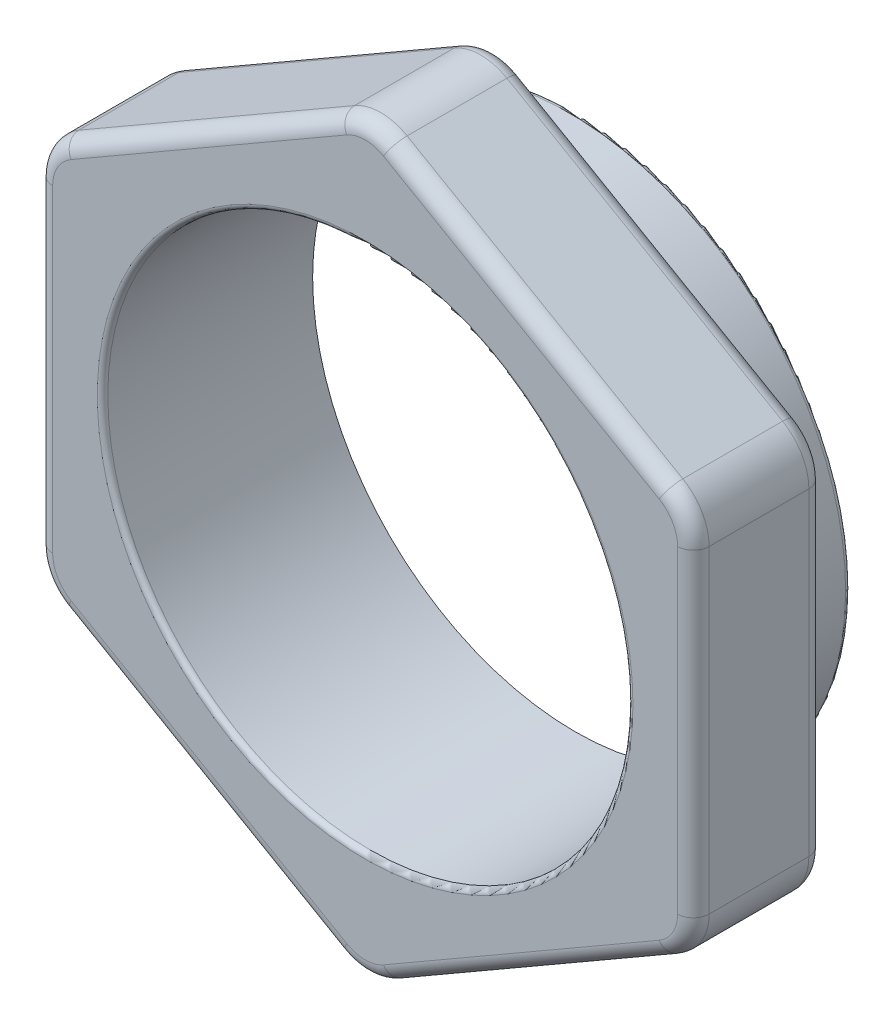
SolidWorks part; units mm, degrees
material "Alloy Steel"
ref_plane "Front Plane" through (0, 0, 0) normal (0, 0, 1) x (1, 0, 0)
ref_plane "Top Plane" through (0, 0, 0) normal (0, 1, 0) x (1, 0, 0)
ref_plane "Right Plane" through (0, 0, 0) normal (1, 0, 0) x (0, 0, -1)
sketch "Sketch1" plane through (0, 0, 0) normal (0, 0, 1) x (1, 0, 0)
  circle A0 centre (0, 0) radius 6.6675
  dimension "D1" = 13.335
extrude "Boss-Extrude1" add sketch "Sketch1" along normal blind 1.905 contours A0
sketch "Sketch2" plane through (0, 0, 1.905) normal (0, 0, 1) x (1, 0, 0)
  line L1 (0, -9.1654) -> (7.9375, -4.5827)
  line L2 (7.9375, -4.5827) -> (7.9375, 4.5827)
  line L3 (7.9375, 4.5827) -> (0, 9.1654)
  line L4 (0, 9.1654) -> (-7.9375, 4.5827)
  line L5 (-7.9375, 4.5827) -> (-7.9375, -4.5827)
  line L6 (-7.9375, -4.5827) -> (0, -9.1654)
  circle A0 centre (0, 0) radius 7.9375 construction
  dimension "D1" = 15.875
extrude "Boss-Extrude2" add sketch "Sketch2" along normal blind 3.175
sketch "Sketch3" plane through (0, 0, 0) normal (0, 0, -1) x (-1, 0, 0)
  circle A0 centre (0, 0) radius 6.35
  dimension "D1" = 12.7
extrude "Cut-Extrude1" cut sketch "Sketch3" against normal through all
fillet "Fillet1" radius 1.27 6 edges at (-7.9375, 4.5827, 3.4925) (-7.9375, -4.5827, 3.4925) (0, -9.1654, 3.4925) (7.9375, -4.5827, 3.4925) (7.9375, 4.5827, 3.4925) (0, 9.1654, 3.4925)
fillet "Fillet2" radius 0.381 12 edges at (0, 8.969, 1.905) (3.9688, 6.8741, 1.905) (7.7674, 4.4845, 1.905) (7.9375, 0, 1.905) (7.7674, -4.4845, 1.905) (3.9687, -6.8741, 1.905) (0, -8.969, 1.905) (-3.9688, -6.8741, 1.905) (-7.7674, -4.4845, 1.905) (-7.9375, 0, 1.905) (-7.7674, 4.4845, 1.905) (-3.9687, 6.8741, 1.905)
fillet "Fillet3" radius 0.381 12 edges at (0, 8.969, 5.08) (3.9688, 6.8741, 5.08) (7.7674, 4.4845, 5.08) (7.9375, 0, 5.08) (7.7674, -4.4845, 5.08) (3.9687, -6.8741, 5.08) (0, -8.969, 5.08) (-3.9688, -6.8741, 5.08) (-7.7674, -4.4845, 5.08) (-7.9375, 0, 5.08) (-7.7674, 4.4845, 5.08) (-3.9687, 6.8741, 5.08)
fillet "Fillet4" radius 0.127 1 edges at (-6.35, 0, 5.08)
fillet "Fillet5" radius 0.127 2 edges at (6.6675, 0, 0) (6.6675, 0, 1.905)
